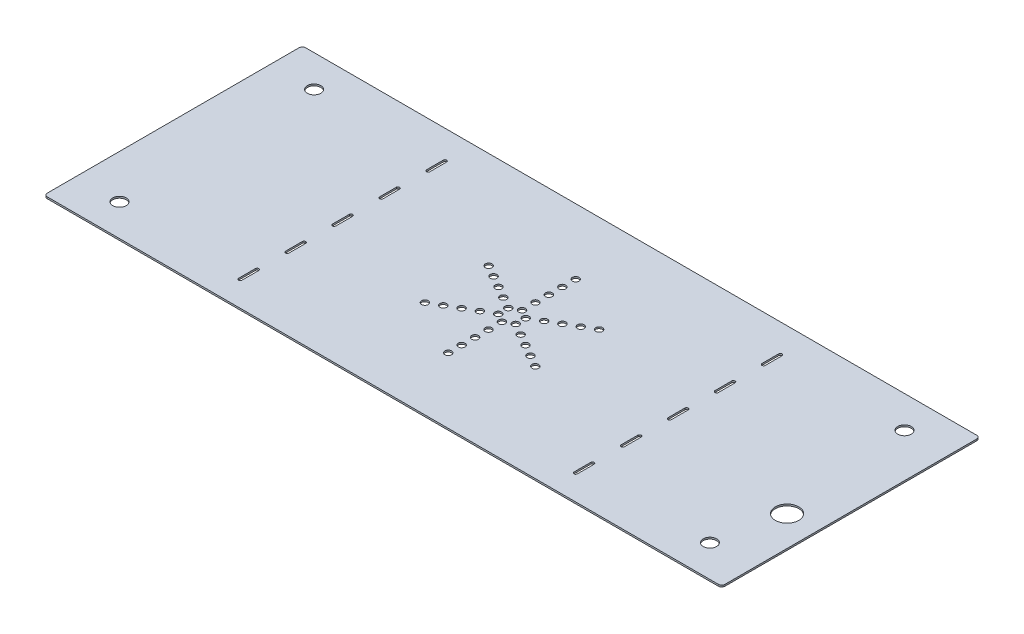
SolidWorks part; units mm, degrees
material "3.0205 (EN-AW 1200)"
ref_plane "Спереди" through (0, 0, 0) normal (0, 0, 1) x (1, 0, 0)
ref_plane "Сверху" through (0, 0, 0) normal (0, 1, 0) x (1, 0, 0)
ref_plane "Справа" through (0, 0, 0) normal (1, 0, 0) x (0, 0, -1)
sketch "Эскиз1" plane through (0, 0, 0) normal (0, 1, 0) x (1, 0, 0)
  line L0 (-50, -38.5) -> (-50, 38.5) construction
  line L1 (-100, 38.5) -> (100, 38.5)
  line L2 (-101, 37.5) -> (-101, -37.5)
  line L3 (-100, -38.5) -> (100, -38.5)
  line L4 (101, 37.5) -> (101, -37.5)
  line L5 (-101, 38.5) -> (101, -38.5) construction
  line L6 (-101, -38.5) -> (101, 38.5) construction
  line L7 (50, -38.5) -> (50, 38.5) construction
  line L8 (-88, 38.5) -> (-88, -38.5) construction
  line L9 (88, 38.5) -> (88, -38.5) construction
  line L10 (-50, -31) -> (-50, -26) construction
  line L11 (-50.5, -31) -> (-50.5, -26)
  line L12 (-49.5, -31) -> (-49.5, -26)
  line L13 (-50, -17) -> (-50, -12) construction
  line L14 (-50.5, -17) -> (-50.5, -12)
  line L15 (-49.5, -17) -> (-49.5, -12)
  line L16 (-50, -24.5) -> (-50, 52.5) construction
  line L28 (50, -31) -> (50, -26) construction
  line L31 (49.5, -31) -> (49.5, -26)
  line L34 (50.5, -31) -> (50.5, -26)
  line L37 (50, -17) -> (50, -12) construction
  line L40 (49.5, -17) -> (49.5, -12)
  line L43 (50.5, -17) -> (50.5, -12)
  line L46 (50, -3) -> (50, 2) construction
  line L49 (49.5, -3) -> (49.5, 2)
  line L52 (50.5, -3) -> (50.5, 2)
  line L55 (50, 11) -> (50, 16) construction
  line L58 (49.5, 11) -> (49.5, 16)
  line L61 (50.5, 11) -> (50.5, 16)
  line L64 (50, 25) -> (50, 30) construction
  line L67 (49.5, 25) -> (49.5, 30)
  line L70 (0, -19.9405) -> (0, 25.9405) construction
  line L71 (0, 3) -> (0, 7) construction
  line L72 (2.5981, 1.5) -> (6.0622, 3.5) construction
  line L73 (2.5981, -1.5) -> (6.0622, -3.5) construction
  line L74 (0, -3) -> (0, -7) construction
  line L75 (-2.5981, -1.5) -> (-6.0622, -3.5) construction
  line L76 (-2.5981, 1.5) -> (-6.0622, 3.5) construction
  line L77 (-50, -3) -> (-50, 2) construction
  line L78 (-50.5, -3) -> (-50.5, 2)
  line L79 (-49.5, -3) -> (-49.5, 2)
  line L80 (-50, 11) -> (-50, 16) construction
  line L81 (-50.5, 11) -> (-50.5, 16)
  line L82 (-49.5, 11) -> (-49.5, 16)
  line L83 (-50, 25) -> (-50, 30) construction
  line L84 (-50.5, 25) -> (-50.5, 30)
  line L85 (-49.5, 25) -> (-49.5, 30)
  line L86 (50.5, 25) -> (50.5, 30)
  line L87 (-50, -10.5) -> (-50, 66.5) construction
  line L88 (-50, 3.5) -> (-50, 80.5) construction
  line L89 (-50, 17.5) -> (-50, 94.5) construction
  circle A0 centre (-88, 29) radius 2
  circle A2 centre (88, 29) radius 2
  circle A3 centre (88, -29) radius 2
  circle A4 centre (-88, -29) radius 2
  circle A5 centre (92, -10) radius 3.5
  arc A6 (-50.5, -31) -> (-49.5, -31) centre (-50, -31) ccw
  arc A7 (-49.5, -26) -> (-50.5, -26) centre (-50, -26) ccw
  arc A8 (-50.5, -17) -> (-49.5, -17) centre (-50, -17) ccw
  arc A9 (-49.5, -12) -> (-50.5, -12) centre (-50, -12) ccw
  arc A46 (101, -37.5) -> (100, -38.5) centre (100, -37.5) cw
  arc A47 (101, 37.5) -> (100, 38.5) centre (100, 37.5) ccw
  arc A48 (-100, -38.5) -> (-101, -37.5) centre (-100, -37.5) cw
  arc A49 (-100, 38.5) -> (-101, 37.5) centre (-100, 37.5) ccw
  circle A50 centre (0, 3) radius 1
  circle A51 centre (0, 7) radius 1
  circle A52 centre (0, 11) radius 1
  circle A53 centre (0, 15) radius 1
  circle A54 centre (0, 19) radius 1
  circle A55 centre (2.5981, 1.5) radius 1
  circle A56 centre (6.0622, 3.5) radius 1
  circle A57 centre (9.5263, 5.5) radius 1
  circle A58 centre (12.9904, 7.5) radius 1
  circle A59 centre (16.4545, 9.5) radius 1
  circle A60 centre (2.5981, -1.5) radius 1
  circle A61 centre (6.0622, -3.5) radius 1
  circle A62 centre (9.5263, -5.5) radius 1
  circle A63 centre (12.9904, -7.5) radius 1
  circle A64 centre (16.4545, -9.5) radius 1
  circle A65 centre (0, -3) radius 1
  circle A66 centre (0, -7) radius 1
  circle A67 centre (0, -11) radius 1
  circle A68 centre (0, -15) radius 1
  circle A69 centre (0, -19) radius 1
  circle A70 centre (-2.5981, -1.5) radius 1
  circle A71 centre (-6.0622, -3.5) radius 1
  circle A72 centre (-9.5263, -5.5) radius 1
  circle A73 centre (-12.9904, -7.5) radius 1
  circle A74 centre (-16.4545, -9.5) radius 1
  circle A75 centre (-2.5981, 1.5) radius 1
  circle A76 centre (-6.0622, 3.5) radius 1
  circle A77 centre (-9.5263, 5.5) radius 1
  circle A78 centre (-12.9904, 7.5) radius 1
  circle A79 centre (-16.4545, 9.5) radius 1
  arc A80 (-50.5, -3) -> (-49.5, -3) centre (-50, -3) ccw
  arc A81 (-49.5, 2) -> (-50.5, 2) centre (-50, 2) ccw
  arc A82 (-50.5, 11) -> (-49.5, 11) centre (-50, 11) ccw
  arc A83 (-49.5, 16) -> (-50.5, 16) centre (-50, 16) ccw
  arc A84 (-50.5, 25) -> (-49.5, 25) centre (-50, 25) ccw
  arc A85 (-49.5, 30) -> (-50.5, 30) centre (-50, 30) ccw
  arc A86 (49.5, -31) -> (50.5, -31) centre (50, -31) ccw
  arc A87 (50.5, -26) -> (49.5, -26) centre (50, -26) ccw
  arc A88 (49.5, -17) -> (50.5, -17) centre (50, -17) ccw
  arc A89 (50.5, -12) -> (49.5, -12) centre (50, -12) ccw
  arc A90 (49.5, -3) -> (50.5, -3) centre (50, -3) ccw
  arc A91 (50.5, 2) -> (49.5, 2) centre (50, 2) ccw
  arc A92 (49.5, 11) -> (50.5, 11) centre (50, 11) ccw
  arc A93 (50.5, 16) -> (49.5, 16) centre (50, 16) ccw
  arc A94 (49.5, 25) -> (50.5, 25) centre (50, 25) ccw
  arc A95 (50.5, 30) -> (49.5, 30) centre (50, 30) ccw
  point P0 (0, 0)
  point P26 (-50, -28.5)
  point P33 (50, -28.5)
  point P36 (-50, -14.5)
  point P55 (50, -14.5)
  point P62 (50, -0.5)
  point P69 (50, 13.5)
  point P76 (50, 27.5)
  point P193 (0, 0)
  point P206 (0, 0)
  point P219 (0, 0)
  point P232 (0, 0)
  point P245 (0, 0)
  point P258 (0, 0)
  point P259 (-50, -0.5)
  point P267 (-50, 13.5)
  point P274 (-50, 27.5)
  dimension "D7" = 4
  dimension "D8" = 4
  dimension "D9" = 4
  dimension "D10" = 4
  dimension "D12" = 9.5
  dimension "D15" = 7
  dimension "D22" = 1
  dimension "D23" = 2
  dimension "D1" = 77
  dimension "D2" = 202
  dimension "D3" = 51
  dimension "D4" = 51
  dimension "D5" = 13
  dimension "D6" = 13
  dimension "D11" = 9.5
  dimension "D13" = 9.5
  dimension "D14" = 9.5
  dimension "D16" = 28.5
  dimension "D17" = 5
  dimension "D18" = 1
  dimension "D19" = 10
  dimension "D24" = 3
  dimension "D26" = 4
  dimension "D20" = 5
  dimension "D21" = 1
  dimension "D25" = 5
  dimension "D27" = 6
extrude "Бобышка-Вытянуть2" add sketch "Эскиз1" along normal blind 0.5
